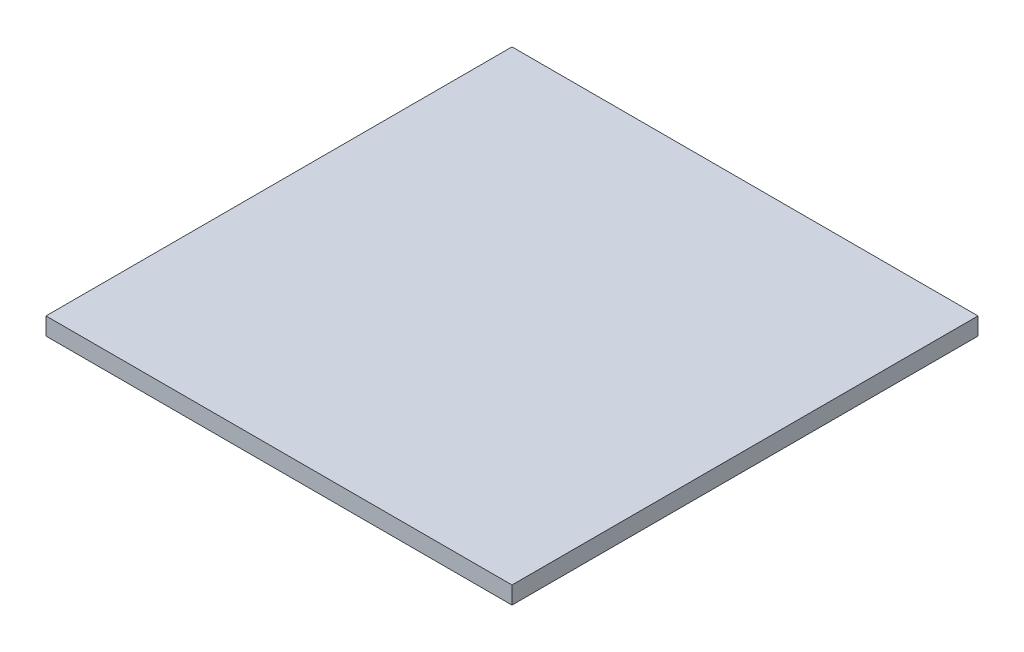
SolidWorks part; units mm, degrees
ref_plane "Front Plane" through (0, 0, 0) normal (0, 0, 1) x (1, 0, 0)
ref_plane "Top Plane" through (0, 0, 0) normal (0, 1, 0) x (1, 0, 0)
ref_plane "Right Plane" through (0, 0, 0) normal (1, 0, 0) x (0, 0, -1)
sketch "Sketch1" plane through (0, 0, 0) normal (0, 1, 0) x (1, 0, 0)
  line L1 (-200, -200) -> (200, -200)
  line L2 (-200, -200) -> (-200, 200)
  line L3 (-200, 200) -> (200, 200)
  line L4 (200, -200) -> (200, 200)
  line L5 (-200, -200) -> (200, 200) construction
  line L6 (-200, 200) -> (200, -200) construction
  point P0 (0, 0)
  dimension "D1" = 400
  dimension "D2" = 400
extrude "Boss-Extrude1" add sketch "Sketch1" along normal blind 15
